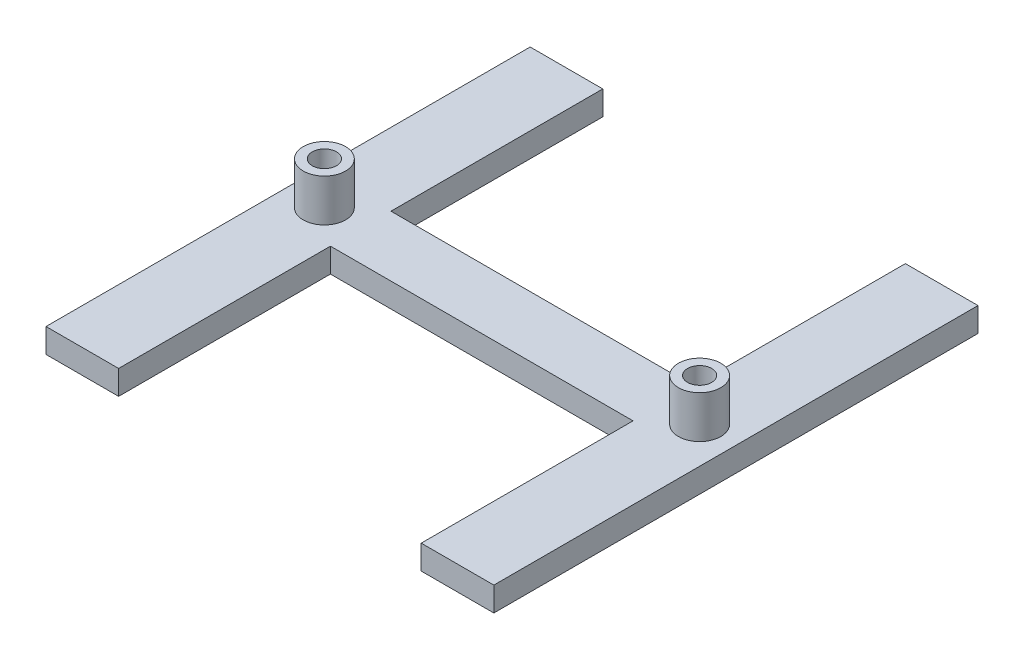
SolidWorks part; units mm, degrees
ref_plane "Front Plane" through (0, 0, 0) normal (0, 0, 1) x (1, 0, 0)
ref_plane "Top Plane" through (0, 0, 0) normal (0, 1, 0) x (1, 0, 0)
ref_plane "Right Plane" through (0, 0, 0) normal (1, 0, 0) x (0, 0, -1)
sketch "Sketch3" plane through (0, 0, 0) normal (0, 1, 0) x (1, 0, 0)
  line L2 (-69.7108, 123.7634) -> (-81.7108, 123.7634)
  line L3 (-81.7108, 123.7634) -> (-81.7108, 43.7634)
  line L4 (-81.7108, 43.7634) -> (-69.7108, 43.7634)
  line L15 (-69.7108, 88.7643) -> (-19.7108, 88.7643)
  line L16 (-19.7108, 88.7643) -> (-19.7108, 78.7625)
  line L17 (-19.7108, 78.7625) -> (-69.7108, 78.7625)
  line L19 (-69.7108, 88.7643) -> (-69.7108, 78.7625)
  line L20 (-69.7108, 123.7634) -> (-69.7108, 43.7634)
  line L21 (-7.7108, 123.7634) -> (-7.7108, 43.7634)
  line L22 (-7.7108, 123.7634) -> (-19.7108, 123.7634)
  line L23 (-19.7108, 123.7634) -> (-19.7108, 43.7634)
  line L24 (-19.7108, 43.7634) -> (-7.7108, 43.7634)
  line L26 (-19.7108, 83.7634) -> (-14.902, 83.7634)
extrude "Boss-Extrude1" add sketch "Sketch3" along normal blind 4
sketch "Sketch4" plane through (0, 4, 0) normal (0, 1, 0) x (1, 0, 0)
  line L0 (-81.7108, 83.7634) -> (-75.7108, 83.7634)
  line L1 (-81.7108, 123.7634) -> (-81.7108, 43.7634) construction
  line L2 (-7.7108, 83.7634) -> (-13.7108, 83.7634)
  line L3 (-7.7108, 123.7634) -> (-7.7108, 43.7634) construction
  circle A0 centre (-75.7108, 83.7634) radius 2
  circle A1 centre (-75.7108, 83.7634) radius 3.5
  circle A2 centre (-13.7108, 83.7634) radius 2
  circle A3 centre (-13.7108, 83.7634) radius 3.5
extrude "Boss-Extrude2" add sketch "Sketch4" along normal blind 7 contours A0 | A1 | A3 | A2
